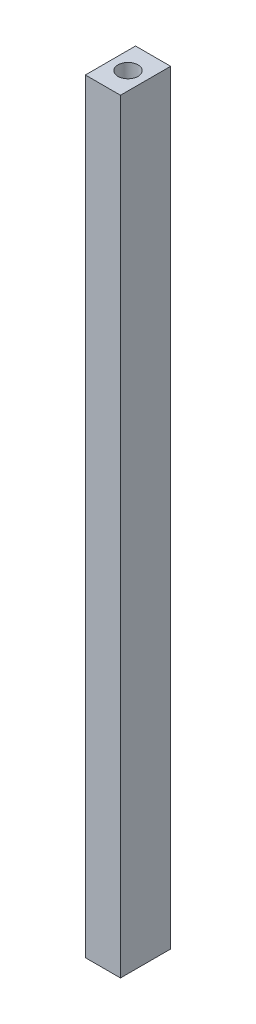
SolidWorks part; units mm, degrees
ref_plane "Front Plane" through (0, 0, 0) normal (0, 0, 1) x (1, 0, 0)
ref_plane "Top Plane" through (0, 0, 0) normal (0, 1, 0) x (1, 0, 0)
ref_plane "Right Plane" through (0, 0, 0) normal (1, 0, 0) x (0, 0, -1)
sketch "Sketch1" plane through (0, 0, 0) normal (0, 1, 0) x (1, 0, 0)
  line L1 (-3.5, -5) -> (3.5, -5)
  line L2 (-3.5, -5) -> (-3.5, 5)
  line L3 (-3.5, 5) -> (3.5, 5)
  line L4 (3.5, -5) -> (3.5, 5)
  line L5 (-3.5, -5) -> (3.5, 5) construction
  line L6 (-3.5, 5) -> (3.5, -5) construction
  point P0 (0, 0)
  dimension "D1" = 7
  dimension "D2" = 10
extrude "Boss-Extrude1" add sketch "Sketch1" along normal mid plane 152.4
sketch "Sketch3" plane through (0, 0, 5) normal (0, 0, 1) x (1, 0, 0)
  line L0 (3.5, 76.2) -> (3.5, -76.2) construction
  line L1 (-3.5, -76.2) -> (3.5, -76.2)
  line L2 (-3.5, -76.2) -> (-3.5, -72.2)
  line L3 (-3.5, -72.2) -> (3.5, -72.2)
  line L4 (3.5, -76.2) -> (3.5, -72.2)
  dimension "D1" = 4
extrude "Boss-Extrude2" [suppressed] add sketch "Sketch3" along normal blind 8
sketch "Sketch4" [suppressed] plane through (0, -72.2, 0) normal (0, 1, 0) x (1, 0, 0)
  line L0 (0, -5) -> (0, -13) construction
  line L1 (3.5, -5) -> (-3.5, -5) construction
  line L2 (3.5, -13) -> (-3.5, -13) construction
  circle A0 centre (0, -9) radius 1.7
  dimension "D1" = 3.4
  dimension "D2" = 4
extrude "Cut-Extrude1" [suppressed] cut sketch "Sketch4" against normal through all
fillet "Fillet1" [suppressed] radius 2
sketch "Sketch5" [suppressed] plane through (0, -72.2, 0) normal (0, 1, 0) x (1, 0, 0)
  circle A0 centre (0, -9) radius 1.7 construction
  circle A1 centre (0, -9) radius 1.7
  circle A2 centre (0, -9) radius 3.5
  dimension "D1" = 7
extrude "Cut-Extrude2" [suppressed] cut sketch "Sketch5" along normal up to next
sketch "Sketch6" plane through (0, -76.2, 0) normal (0, -1, 0) x (1, 0, 0)
  circle A0 centre (0, 0) radius 2
  dimension "D1" = 4
extrude "Cut-Extrude3" cut sketch "Sketch6" against normal blind 13
mirror "Mirror1" about plane through (0, 0, 0) normal (0, 1, 0) of "Cut-Extrude3", "Boss-Extrude2", "Cut-Extrude1", "Cut-Extrude2", "Fillet1"
